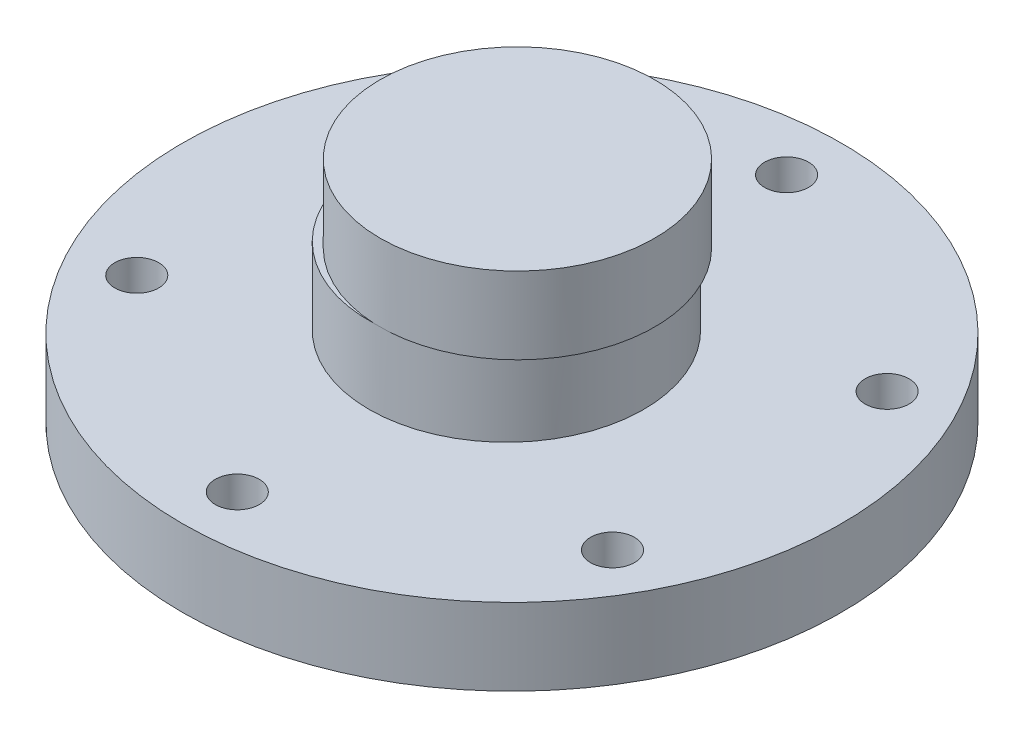
SolidWorks part; units mm, degrees
ref_plane "Front Plane" through (0, 0, 0) normal (0, 0, 1) x (1, 0, 0)
ref_plane "Top Plane" through (0, 0, 0) normal (0, 1, 0) x (1, 0, 0)
ref_plane "Right Plane" through (0, 0, 0) normal (1, 0, 0) x (0, 0, -1)
sketch "Sketch1" plane through (0, 0, 0) normal (0, 1, 0) x (1, 0, 0)
  circle A0 centre (0, 0) radius 25 construction
  circle A1 centre (0, 0) radius 30
  circle A2 centre (0, 25) radius 2
  circle A3 centre (21.6506, 12.5) radius 2
  circle A4 centre (21.6506, -12.5) radius 2
  circle A5 centre (0, -25) radius 2
  circle A6 centre (-21.6506, -12.5) radius 2
  circle A7 centre (-21.6506, 12.5) radius 2
  point P18 (0, 0)
  dimension "D1" = 50
  dimension "D2" = 60
  dimension "D3" = 4
  dimension "D4" = 6
extrude "Boss-Extrude1" add sketch "Sketch1" along normal blind 7
sketch "Sketch2" plane through (0, 7, 0) normal (0, 1, 0) x (1, 0, 0)
  circle A0 centre (-0.5, 0) radius 12.5
  point P0 (0, 0)
  point P1 (-0.5, 0)
  dimension "D2" = 25
  dimension "D1" = 0.5
extrude "Boss-Extrude2" add sketch "Sketch2" along normal blind 7
sketch "Sketch3" plane through (0, 14, 0) normal (0, 1, 0) x (1, 0, 0)
  circle A0 centre (0.5, 0) radius 12.5
  point P0 (0.5, 0)
  dimension "D2" = 25
  dimension "D1" = 0.5
extrude "Boss-Extrude3" add sketch "Sketch3" along normal blind 7
